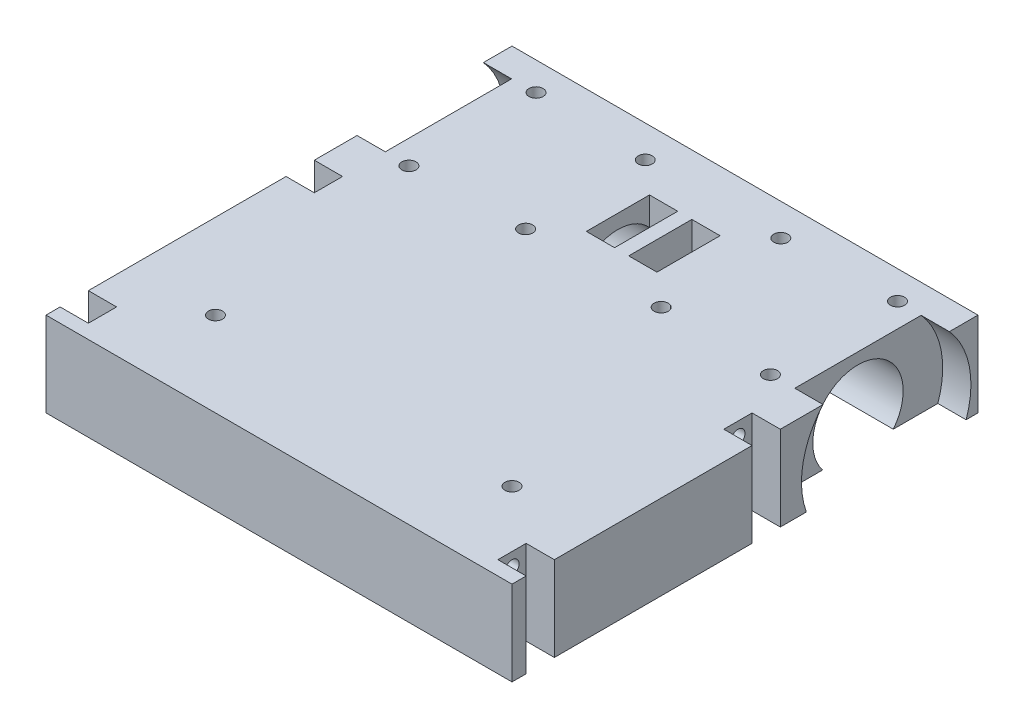
SolidWorks part; units mm, degrees
ref_plane "Plan de face" through (0, 0, 0) normal (0, 0, 1) x (1, 0, 0)
ref_plane "Plan de dessus" through (0, 0, 0) normal (0, 1, 0) x (1, 0, 0)
ref_plane "Plan de droite" through (0, 0, 0) normal (1, 0, 0) x (0, 0, -1)
sketch "Esquisse2" plane through (0, 0, 0) normal (0, 1, 0) x (1, 0, 0)
  line L1 (82.5, 82.5) -> (-82.5, 82.5)
  line L2 (82.5, 82.5) -> (82.5, -82.5)
  line L3 (82.5, -82.5) -> (-82.5, -82.5)
  line L4 (-82.5, 82.5) -> (-82.5, -82.5)
  line L5 (82.5, 82.5) -> (-82.5, -82.5) construction
  line L6 (82.5, -82.5) -> (-82.5, 82.5) construction
  point P0 (0, 0)
  dimension "D1" = 165
  dimension "D2" = 165
extrude "BASE" add sketch "Esquisse2" along normal blind 30
sketch "Esquisse3" plane through (82.5, 0, 0) normal (1, 0, 0) x (0, 0, -1)
  line L0 (82.5, 10) -> (31.0775, 10) construction
  line L1 (82.5, 30) -> (82.5, 0) construction
  line L2 (-82.5, 0) -> (82.5, 0) construction
  circle A0 centre (50, 10) radius 15
  point P4 (50, 10)
  dimension "D3" = 30
  dimension "D1" = 32.5
  dimension "D2" = 10
extrude "BLOC MOTEUR 1." cut sketch "Esquisse3" against normal blind 80
sketch "Esquisse4" plane through (0, 0, 0) normal (0, -1, 0) x (1, 0, 0)
  line L0 (2.5, -61.1803) -> (82.5, -61.1803) construction
  line L1 (2.5, -38.8197) -> (12.5, -38.8197)
  line L2 (2.5, -38.8197) -> (2.5, -61.1803)
  line L3 (2.5, -61.1803) -> (12.5, -61.1803)
  line L4 (12.5, -38.8197) -> (12.5, -61.1803)
  dimension "D1" = 10
extrude "ACCES MOTEUR" cut sketch "Esquisse4" against normal blind 37
ref_plane "PLAN SYM " through (0, 0, 0) normal (1, 0, 0) x (0, 0, -1)
sketch "Esquisse6" plane through (82.5, 0, 0) normal (1, 0, 0) x (0, 0, -1)
  line L0 (35, 10) -> (65, 10) construction
  arc A0 (38.8197, 20) -> (38.8197, 0) centre (50, 10) ccw construction
  arc A1 (61.1803, 0) -> (38.8197, 0) centre (50, 10) ccw construction
  circle A2 centre (50, 10) radius 16.01
  dimension "D1" = 32.02
extrude "BLOC MOTEUR 2" cut sketch "Esquisse6" against normal blind 37
mirror "SYM BLOC MOTEUR" about plane through (0, 0, 0) normal (1, 0, 0) of "ACCES MOTEUR", "BLOC MOTEUR 1.", "BLOC MOTEUR 2"
sketch "Esquisse7" plane through (0, 0, 0) normal (0, -1, 0) x (1, 0, 0)
  line L0 (-64, -37.4972) -> (-64, -72.5028) construction
  line L1 (-82.5, -37.4972) -> (-45.5, -37.4972) construction
  line L2 (-24, -38.8197) -> (-24, -67.469) construction
  line L3 (-45.5, -38.8197) -> (-2.5, -38.8197) construction
  line L4 (-45.5, -62.5028) -> (-82.5, -62.5028) construction
  line L5 (-2.5, -61.1803) -> (-45.5, -61.1803) construction
  line L6 (-64, -37.4972) -> (-64, -13.9891) construction
  line L7 (-24, -71.1803) -> (-24, -20.9291) construction
  circle A0 centre (-64, -27.4972) radius 2.5
  circle A1 centre (-24, -28.8197) radius 2.5
  circle A2 centre (-24, -71.1803) radius 2.5
  circle A3 centre (-64, -72.5028) radius 2.5
  point P8 (-64, -27.4972)
  point P9 (-64, -72.5028)
  point P10 (-24, -71.1803)
  point P11 (-24, -28.8197)
  dimension "D5" = 5
  dimension "D6" = 5
  dimension "D7" = 5
  dimension "D8" = 5
  dimension "D1" = 10
  dimension "D2" = 10
  dimension "D3" = 10
  dimension "D4" = 10
extrude "VIS MOTEUR" cut sketch "Esquisse7" against normal through all
mirror "SYM VIS" about plane through (0, 0, 0) normal (1, 0, 0) of "VIS MOTEUR"
sketch "Esquisse8" plane through (0, 0, 0) normal (0, -1, 0) x (1, 0, 0)
  line L0 (-82.5, 82.5) -> (82.5, 82.5) construction
  line L1 (-82.5, -37.4972) -> (-82.5, 82.5) construction
  line L2 (82.5, 82.5) -> (82.5, -37.4972) construction
  circle A0 centre (-52.5, 52.5) radius 2.5
  circle A1 centre (52.5, 52.5) radius 2.5
  point P0 (-52.5, 52.5)
  point P1 (52.5, 52.5)
  dimension "D5" = 5
  dimension "D6" = 5
  dimension "D1" = 30
  dimension "D2" = 30
  dimension "D3" = 30
  dimension "D4" = 30
extrude "VIS PATIN" cut sketch "Esquisse8" against normal through all
sketch "Esquisse12" plane through (-82.5, 0, 0) normal (-1, 0, 0) x (0, 0, 1)
  circle A0 centre (-50, 10) radius 30
  dimension "D1" = 60
extrude "ESPACE ROUE " cut sketch "Esquisse12" against normal blind 10
mirror "SYM ESPACE ROUE" about plane through (0, 0, 0) normal (1, 0, 0) of "ESPACE ROUE "
sketch "Esquisse23" plane through (82.5, 0, 0) normal (1, 0, 0) x (0, 0, -1)
  line L0 (20.0461, 11.6625) -> (20.0461, -3.5531) construction
  line L1 (-77.5, 30) -> (-67.5, 30)
  line L2 (-77.5, 30) -> (-77.5, 0)
  line L3 (-77.5, 0) -> (-67.5, 0)
  line L4 (-67.5, 30) -> (-67.5, 0)
  line L6 (-82.5, 0) -> (21.7157, 0) construction
  line L8 (-82.5, 30) -> (-82.5, 0) construction
  line L9 (-82.5, 30) -> (27.6393, 30) construction
  line L10 (12.5, 0) -> (2.5, 0)
  line L11 (12.5, 0) -> (12.5, 30)
  line L12 (12.5, 30) -> (2.5, 30)
  line L13 (2.5, 0) -> (2.5, 30)
  arc A1 (27.6393, 30) -> (21.7157, 0) centre (50, 10) ccw construction
  point P19 (7.5, 0)
  dimension "D1" = 5
  dimension "D2" = 10
  dimension "D4" = 10
  dimension "D5" = 90
extrude "VIDE TIGE" cut sketch "Esquisse23" against normal blind 10
mirror "SYM TIGE" about plane through (0, 0, 0) normal (1, 0, 0) of "VIDE TIGE"
sketch "Esquisse25" plane through (72.5, 0, 0) normal (1, 0, 0) x (0, 0, -1)
  line L0 (-77.5, 30) -> (-67.5, 0) construction
  line L1 (-67.5, 0) -> (-72.5, 0) construction
  line L2 (-77.5, 0) -> (-67.5, 0) construction
  line L3 (-72.5, 0) -> (-72.5, 30) construction
  line L4 (-67.5, 30) -> (-77.5, 30) construction
  line L5 (2.5, 30) -> (-67.5, 0) construction
  line L6 (-67.5, 0) -> (-67.5, 30) construction
  line L7 (-67.5, 30) -> (-32.5, 30) construction
  line L8 (-67.5, 30) -> (2.5, 30) construction
  line L9 (-32.5, 30) -> (-32.5, -2.9576) construction
  circle A0 centre (-72.5, 25) radius 2.5
  circle A1 centre (-72.5, 15) radius 2.5
  circle A2 centre (-72.5, 5) radius 2.5
  circle A3 centre (7.5, 5) radius 2.5
  circle A4 centre (7.5, 25) radius 2.5
  circle A5 centre (7.5, 15) radius 2.5
  dimension "D1" = 5
  dimension "D2" = 5
  dimension "D3" = 5
  dimension "D4" = 10
  dimension "D5" = 10
  dimension "D6" = 5
extrude "VIDE VIS" cut sketch "Esquisse25" against normal up to next
